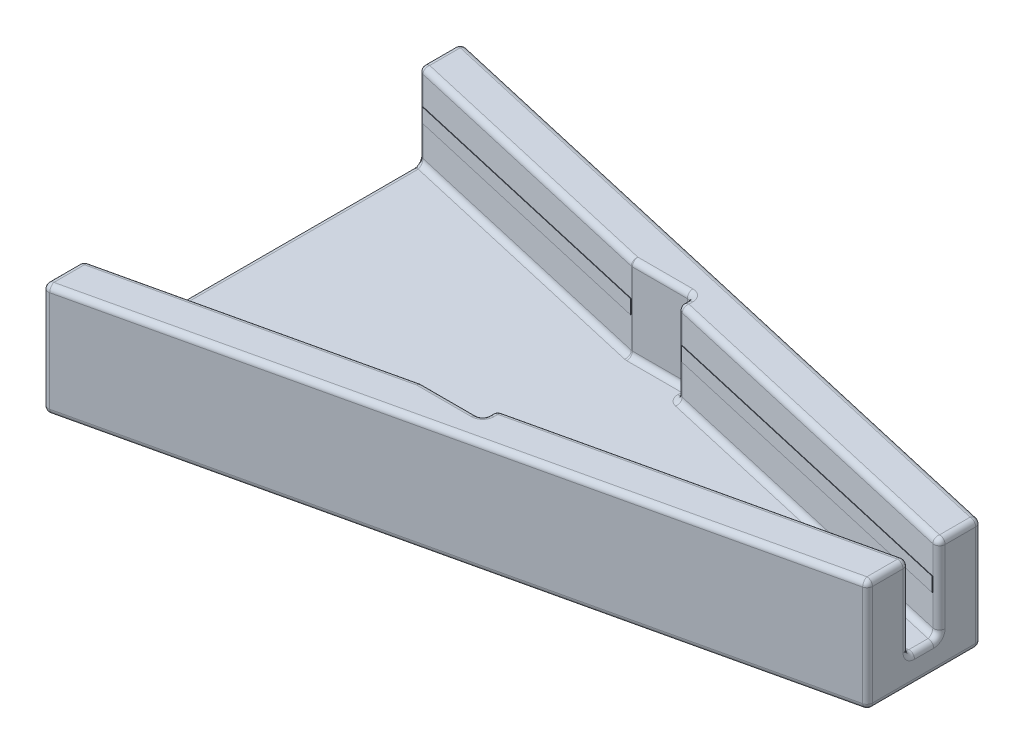
SolidWorks part; units mm, degrees
ref_plane "Front Plane" through (0, 0, 0) normal (0, 0, 1) x (1, 0, 0)
ref_plane "Top Plane" through (0, 0, 0) normal (0, 1, 0) x (1, 0, 0)
ref_plane "Right Plane" through (0, 0, 0) normal (1, 0, 0) x (0, 0, -1)
sketch "Sketch1" plane through (0, 0, 0) normal (0, 1, 0) x (1, 0, 0)
  line L0 (0, 95.25) -> (0, -95.25)
  line L1 (0, -95.25) -> (304.8, -25.4)
  line L2 (304.8, -25.4) -> (304.8, 25.4)
  line L3 (304.8, 25.4) -> (0, 95.25)
  point P4 (0, 0)
  point P6 (304.8, 0)
  dimension "D1" = 304.8
  dimension "D2" = 190.5
  dimension "D3" = 50.8
extrude "Boss-Extrude1" add sketch "Sketch1" along normal blind 12.7
sketch "Sketch2" plane through (0, 12.7, 0) normal (0, 1, 0) x (1, 0, 0)
  line L1 (0, 76.2) -> (304.8, 6.35)
  line L2 (0, 95.25) -> (0, -95.25) construction
  line L3 (304.8, -25.4) -> (304.8, 25.4) construction
  line L4 (304.8, 25.4) -> (0, 95.25) construction
  line L5 (304.8, -6.35) -> (0, -76.2)
  line L6 (0, -95.25) -> (304.8, -25.4) construction
  line L7 (304.8, -25.4) -> (304.8, -6.35)
  line L8 (0, -95.25) -> (304.8, -25.4)
  line L9 (304.8, 25.4) -> (0, 95.25)
  line L10 (0, 95.25) -> (0, 76.2)
  line L11 (0, -76.2) -> (0, -95.25)
  line L12 (304.8, 6.35) -> (304.8, 25.4)
  dimension "D1" = 19.05
  dimension "D2" = 19.05
extrude "Boss-Extrude2" add sketch "Sketch2" along normal blind 38.1
sketch "Sketch3" plane through (0, 50.8, 0) normal (0, 1, 0) x (1, 0, 0)
  line L0 (152.4, 47.625) -> (152.4, -47.625) construction
  line L2 (152.4, 47.625) -> (103.6889, 47.625)
  line L3 (152.4, 47.625) -> (152.4, -47.625)
  line L4 (152.4, -47.625) -> (103.6889, -47.625)
  line L5 (103.6889, 47.625) -> (103.6889, -47.625)
  line L7 (0, 76.2) -> (304.8, 6.35) construction
  point P2 (152.4, 0)
  point P5 (0, 0)
  point P8 (152.4, 41.275)
  dimension "D1" = 95.25
  dimension "D2" = 6.35
extrude "Cut-Extrude1" cut sketch "Sketch3" against normal up to surface (38.1 mm away) up to face at (152.4, 12.7, 0)
ref_plane "Plane1" through (0, 35.56, 0) normal (0, 1, 0) x (1, 0, 0)
fillet "Fillet1" radius 2.54 42 edges at (152.4, 31.75, -41.275) (124.6909, 31.75, -47.625) (152.4, 31.75, -47.625) (152.4, 0, 60.325) (0, 31.75, -76.2) (0, 25.4, 95.25) (0, 0, 0) (304.8, 25.4, 25.4) (304.8, 31.75, -6.35) (304.8, 0, 0) (304.8, 25.4, -25.4) (0, 25.4, -95.25) (152.4, 0, -60.325) (138.5455, 50.8, -47.625) (62.3455, 50.8, -61.9125) (0, 50.8, -85.725) (152.4, 50.8, -60.325) (304.8, 50.8, -15.875) (228.6, 50.8, -23.8125) (152.4, 50.8, -44.45) (0, 12.7, 0) (62.3455, 12.7, -61.9125) (138.5455, 12.7, -47.625) (152.4, 12.7, -44.45) (228.6, 12.7, -23.8125) (304.8, 12.7, 0) (152.4, 12.7, 44.45) (152.4, 50.8, 44.45) (304.8, 31.75, 6.35) (152.4, 31.75, 41.275) (228.6, 12.7, 23.8125) (138.5455, 50.8, 47.625) (138.5455, 12.7, 47.625) (152.4, 31.75, 47.625) (0, 31.75, 76.2) (62.3455, 12.7, 61.9125) (124.6909, 31.75, 47.625) (228.6, 50.8, 23.8125) (304.8, 50.8, 15.875) (152.4, 50.8, 60.325) (0, 50.8, 85.725) (62.3455, 50.8, 61.9125)
sketch "Sketch4" plane through (0, 35.56, 0) normal (0, 1, 0) x (1, 0, 0)
  line L0 (304.8, -6.35) -> (152.4, -41.275) construction
  line L1 (124.6909, -47.625) -> (0, -76.2) construction
  line L2 (152.4, 41.275) -> (304.8, 6.35) construction
  line L3 (0, 76.2) -> (124.6909, 47.625) construction
  line L4 (301.6926, -7.0621) -> (154.3726, -40.8229)
  line L5 (124.4109, -47.6892) -> (1.9726, -75.7479)
  line L6 (154.3726, 40.8229) -> (301.6926, 7.0621)
  line L7 (1.9726, 75.7479) -> (124.4109, 47.6892)
  line L8 (1.9159, 75.5004) -> (124.3541, 47.4416)
  line L9 (154.3159, 40.5754) -> (301.6359, 6.8145)
  line L10 (124.3541, -47.4416) -> (1.9726, -75.4874)
  line L11 (301.6359, -6.8145) -> (154.3726, -40.5624)
  line L12 (1.9726, 75.7479) -> (1.9159, 75.5004)
  line L22 (124.4109, 47.6892) -> (124.3541, 47.4416)
  line L23 (124.4109, 47.6892) -> (123.8435, 45.2134) construction
  line L24 (0, 76.2) -> (124.6909, 47.625) construction
  line L25 (-0.0567, 75.9524) -> (124.6342, 47.3774) construction
  line L26 (154.3726, 40.8229) -> (154.3159, 40.5754)
  line L27 (153.8052, 38.3471) -> (154.3726, 40.8229) construction
  line L28 (301.6926, 7.0621) -> (301.6359, 6.8145)
  line L29 (301.6926, -7.0621) -> (301.6359, -6.8145)
  line L30 (154.3726, -40.8229) -> (154.3726, -40.5624)
  line L31 (124.4109, -47.6892) -> (124.3541, -47.4416)
  line L32 (1.9726, -75.7479) -> (1.9726, -75.4874)
  line L33 (124.6342, -47.3774) -> (-0.0567, -75.9524) construction
  line L34 (124.6909, -47.625) -> (0, -76.2) construction
  line L35 (304.7433, -6.1024) -> (152.3433, -41.0274) construction
  line L36 (304.8, -6.35) -> (152.4, -41.275) construction
  line L37 (152.4, 41.275) -> (304.8, 6.35) construction
  line L38 (152.3433, 41.0274) -> (304.7433, 6.1024) construction
  dimension "D1" = 0.254
extrude "Boss-Extrude3" add sketch "Sketch4" against normal blind 6.35
